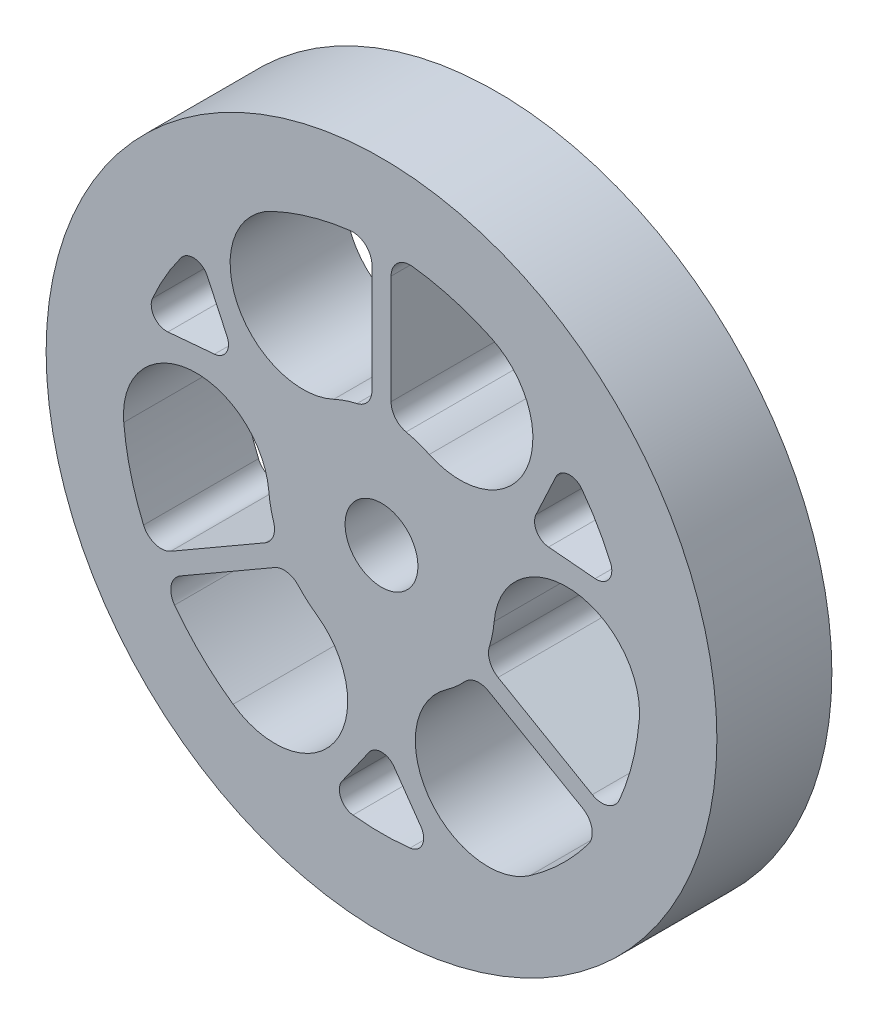
SolidWorks part; units mm, degrees
material "ABS"
ref_plane "Front Plane" through (0, 0, 0) normal (0, 0, 1) x (1, 0, 0)
ref_plane "Top Plane" through (0, 0, 0) normal (0, 1, 0) x (1, 0, 0)
ref_plane "Right Plane" through (0, 0, 0) normal (1, 0, 0) x (0, 0, -1)
sketch "Sketch1" plane through (0, 0, 0) normal (0, 0, 1) x (1, 0, 0)
  circle A0 centre (0, 0) radius 22.225
  dimension "D1" = 44.45
extrude "Boss-Extrude1" add sketch "Sketch1" along normal blind 7.62
sketch "Sketch2" plane through (0, 0, 7.62) normal (0, 0, 1) x (1, 0, 0)
  line L0 (0, 0) -> (0, 22.225) construction
  line L1 (11.5463, 9.6792) -> (10.2369, 6.8713)
  line L2 (11.0692, 5.4298) -> (14.1556, 5.1598)
  line L3 (0, 0) -> (19.2474, 11.1125) construction
  line L4 (12.2721, -1.0737) -> (19.2474, 11.1125) construction
  line L5 (19.2474, 11.1125) -> (5.2062, 11.1648) construction
  line L6 (2.6093, -14.839) -> (0.8323, -12.3011)
  line L7 (-0.8323, -12.3011) -> (-2.6093, -14.839)
  line L8 (-14.1556, 5.1598) -> (-11.0692, 5.4298)
  line L9 (-10.2369, 6.8713) -> (-11.5463, 9.6792)
  circle A0 centre (0, 0) radius 2.413
  arc A1 (5.2062, 11.1648) -> (-5.2062, 11.1648) centre (0, 0) ccw construction
  arc A2 (7.2458, 15.5386) -> (-7.2458, 15.5386) centre (0, 0) ccw
  arc A3 (3.1667, 6.791) -> (-3.1667, 6.791) centre (0, 0) ccw
  arc A4 (3.1667, 6.791) -> (7.2458, 15.5386) centre (5.2062, 11.1648) ccw
  arc A5 (-7.2458, 15.5386) -> (-3.1667, 6.791) centre (-5.2062, 11.1648) ccw
  circle A6 centre (0, 0) radius 22.225 construction
  arc A7 (7.0659, -10.0911) -> (12.2721, -1.0737) centre (0, 0) ccw construction
  arc A8 (9.834, -14.0444) -> (17.0798, -1.4943) centre (0, 0) ccw
  arc A9 (4.2978, -6.1379) -> (7.4645, -0.6531) centre (0, 0) ccw
  arc A10 (4.2978, -6.1379) -> (9.834, -14.0444) centre (7.0659, -10.0911) ccw
  arc A11 (17.0798, -1.4943) -> (7.4645, -0.6531) centre (12.2721, -1.0737) ccw
  arc A12 (-12.2721, -1.0737) -> (-7.0659, -10.0911) centre (0, 0) ccw construction
  arc A13 (-17.0798, -1.4943) -> (-9.834, -14.0444) centre (0, 0) ccw
  arc A14 (-7.4645, -0.6531) -> (-4.2978, -6.1379) centre (0, 0) ccw
  arc A15 (-7.4645, -0.6531) -> (-17.0798, -1.4943) centre (-12.2721, -1.0737) ccw
  arc A16 (-9.834, -14.0444) -> (-4.2978, -6.1379) centre (-7.0659, -10.0911) ccw
  arc A17 (13.283, 9.8552) -> (15.1764, 6.5758) centre (0, 0) cw
  arc A18 (15.1764, 6.5758) -> (14.1556, 5.1598) centre (14.2442, 6.1719) cw
  arc A19 (10.2369, 6.8713) -> (11.0692, 5.4298) centre (11.1577, 6.4419) ccw
  arc A20 (13.283, 9.8552) -> (11.5463, 9.6792) centre (12.4671, 9.2499) ccw
  arc A21 (1.8934, -16.4311) -> (2.6093, -14.839) centre (1.7771, -15.4217) ccw
  arc A22 (1.8934, -16.4311) -> (-1.8934, -16.4311) centre (0, 0) cw
  arc A23 (-1.8934, -16.4311) -> (-2.6093, -14.839) centre (-1.7771, -15.4217) cw
  arc A24 (0.8323, -12.3011) -> (-0.8323, -12.3011) centre (0, -12.8838) ccw
  arc A25 (-15.1764, 6.5758) -> (-14.1556, 5.1598) centre (-14.2442, 6.1719) ccw
  arc A26 (-15.1764, 6.5758) -> (-13.283, 9.8552) centre (0, 0) cw
  arc A27 (-13.283, 9.8552) -> (-11.5463, 9.6792) centre (-12.4671, 9.2499) cw
  arc A28 (-11.0692, 5.4298) -> (-10.2369, 6.8713) centre (-11.1577, 6.4419) ccw
  point P5 (0, 12.319)
  point P18 (10.6686, -6.1595)
  point P25 (-10.6686, -6.1595)
  point P30 (0, 0)
  point P37 (15.7598, 5.0194)
  point P40 (9.6237, 5.5562)
  point P43 (12.2268, 11.1387)
  point P64 (0, 0)
  dimension "D1" = 4.826
  dimension "D2" = 5.08
  dimension "D3" = 5.08
  dimension "D5" = 3
  dimension "D6" = 1.016
  dimension "D4" = 50
  dimension "D7" = 3
extrude "Cut-Extrude1" cut sketch "Sketch2" against normal through all
sketch "Sketch3" plane through (0, 0, 7.62) normal (0, 0, 1) x (1, 0, 0)
  line L0 (0, 6.223) -> (0, 7.493)
  line L1 (0, 7.493) -> (0, 17.145)
  line L2 (5.3893, -3.1115) -> (6.4891, -3.7465)
  line L3 (6.4891, -3.7465) -> (14.848, -8.5725)
  line L4 (-5.3893, -3.1115) -> (-6.4891, -3.7465)
  line L5 (-6.4891, -3.7465) -> (-14.848, -8.5725)
  arc A0 (3.1667, 6.791) -> (-3.1667, 6.791) centre (0, 0) ccw construction
  arc A1 (7.2458, 15.5386) -> (-7.2458, 15.5386) centre (0, 0) ccw construction
  point P17 (0, 0)
  dimension "D1" = 1.27
  dimension "D2" = 3
extrude "Extrude-Thin1" add sketch "Sketch3" against normal blind 7.62 thin thin type mid plane wall 1.27
fillet "Fillet1" radius 1.27 12 edges at (-0.635, 7.466, 3.81) (0.635, 7.466, 3.81) (0.635, 17.1332, 3.81) (-0.635, 17.1332, 3.81) (15.1553, -8.0167, 3.81) (14.5203, -9.1165, 3.81) (6.1483, -4.2829, 3.81) (6.7833, -3.1831, 3.81) (-15.1553, -8.0167, 3.81) (-14.5203, -9.1165, 3.81) (-6.1483, -4.2829, 3.81) (-6.7833, -3.1831, 3.81)
